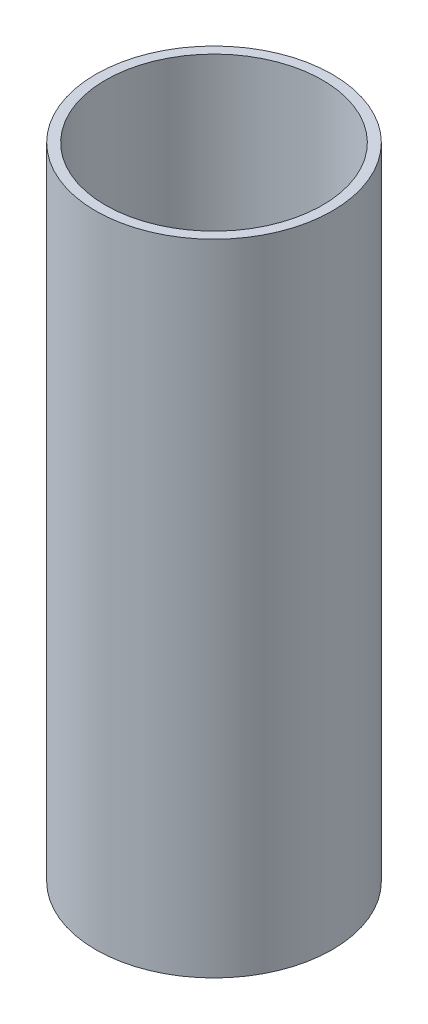
SolidWorks part; units mm, degrees
material "Glass"
ref_plane "Front Plane" through (0, 0, 0) normal (0, 0, 1) x (1, 0, 0)
ref_plane "Top Plane" through (0, 0, 0) normal (0, 1, 0) x (1, 0, 0)
ref_plane "Right Plane" through (0, 0, 0) normal (1, 0, 0) x (0, 0, -1)
sketch "Sketch1" plane through (0, 0, 0) normal (0, 1, 0) x (1, 0, 0)
  circle A0 centre (0, 0) radius 76.2
  circle A1 centre (0, 0) radius 69.85
  dimension "D1" = 152.4
  dimension "D2" = 139.7
extrude "Boss-Extrude1" add sketch "Sketch1" along normal blind 412
